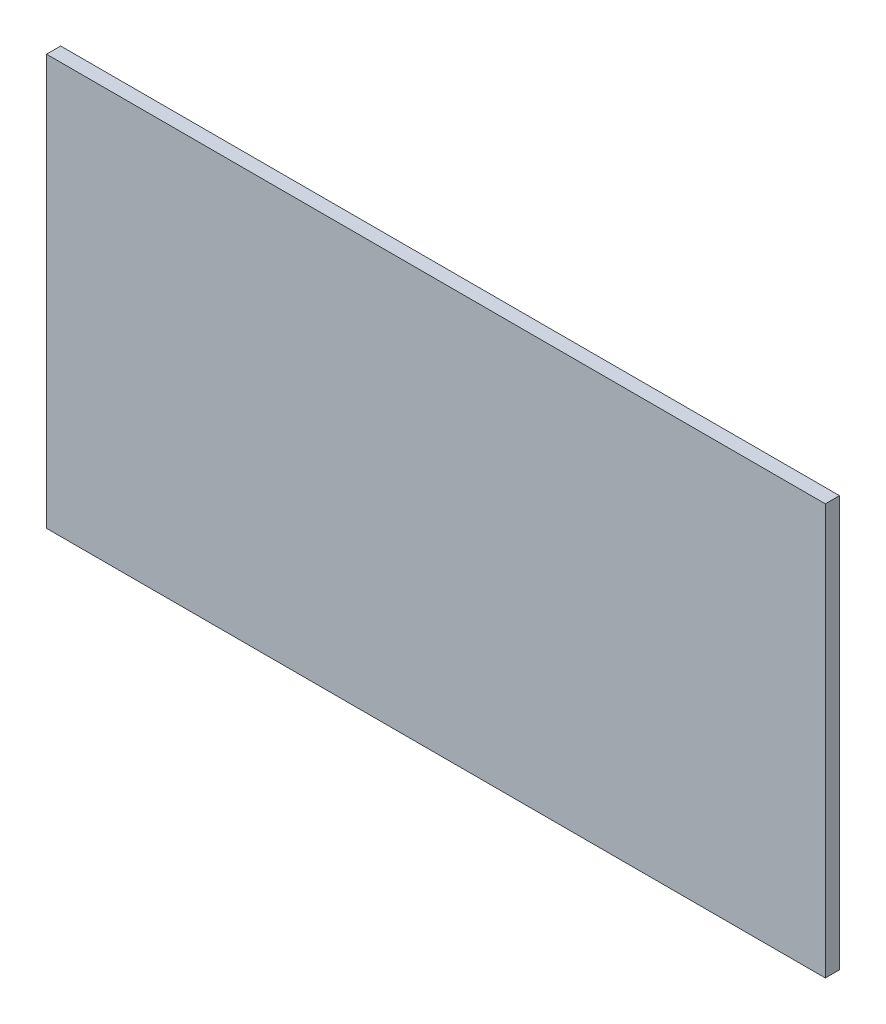
SolidWorks part; units mm, degrees
ref_plane "Plan de face" through (0, 0, 0) normal (0, 0, 1) x (1, 0, 0)
ref_plane "Plan de dessus" through (0, 0, 0) normal (0, 1, 0) x (1, 0, 0)
ref_plane "Plan de droite" through (0, 0, 0) normal (1, 0, 0) x (0, 0, -1)
sketch "Esquisse1" plane through (0, 0, 0) normal (0, 0, 1) x (1, 0, 0)
  line L1 (0, 0) -> (-330, 0)
  line L2 (0, 0) -> (0, 174)
  line L3 (0, 174) -> (-330, 174)
  line L4 (-330, 0) -> (-330, 174)
  dimension "D1" = 174
  dimension "D2" = 330
extrude "Boss.-Extru.1" add sketch "Esquisse1" along normal blind 6
